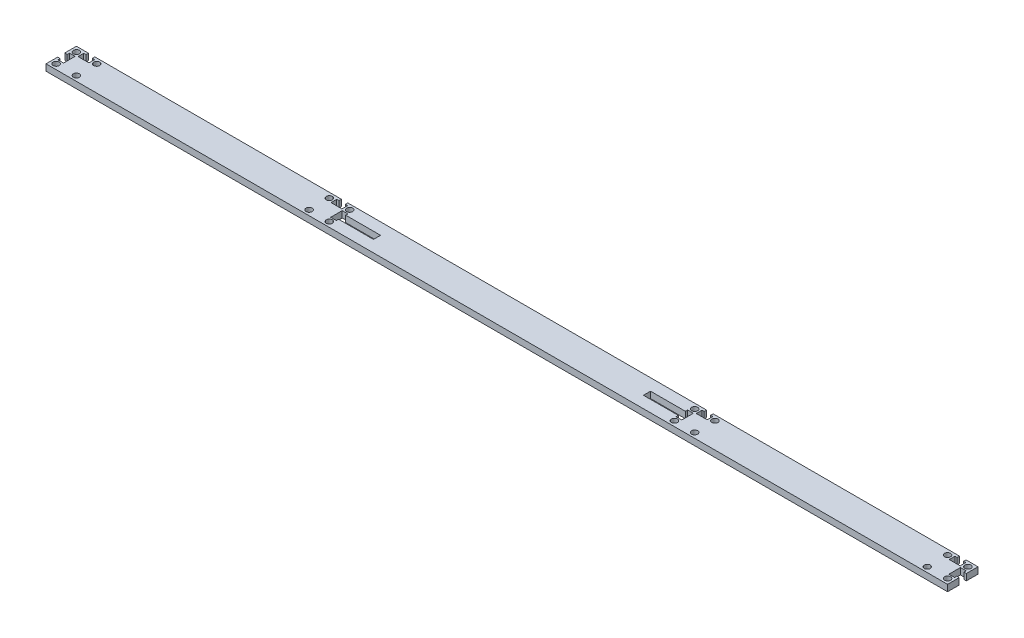
SolidWorks part; units mm, degrees
ref_plane "Front Plane" through (0, 0, 0) normal (0, 0, 1) x (1, 0, 0)
ref_plane "Top Plane" through (0, 0, 0) normal (0, 1, 0) x (1, 0, 0)
ref_plane "Right Plane" through (0, 0, 0) normal (1, 0, 0) x (0, 0, -1)
sketch "Sketch1" plane through (0, 0, 0) normal (0, 1, 0) x (1, 0, 0)
  line L0 (139.7, 7.5) -> (132.2, 7.5)
  line L1 (0, 0) -> (139.7, 0)
  line L2 (0, 0) -> (0, 15)
  line L3 (0, 15) -> (139.7, 15)
  line L4 (139.7, 0) -> (139.7, 15)
  line L5 (0, 7.5) -> (7.5, 7.5)
  line L6 (7.5, 7.5) -> (7.5, 12.5)
  line L7 (7.5, 12.5) -> (2.5, 12.5)
  line L8 (7.5, 12.5) -> (12.5, 12.5)
  line L9 (7.5, 7.5) -> (7.5, 2.5)
  line L10 (7.5, 2.5) -> (2.5, 2.5)
  line L11 (7.5, 2.5) -> (12.5, 2.5)
  line L12 (69.85, 0) -> (69.85, 15)
  line L13 (139.7, 0) -> (139.7, 15)
  line L14 (139.7, 0) -> (304.8, 0)
  line L15 (139.7, 15) -> (304.8, 15)
  line L16 (222.25, 0) -> (222.25, 15)
  line L17 (304.8, 0) -> (304.8, 15)
  line L18 (444.5, 15) -> (304.8, 15)
  line L19 (304.8, 0) -> (304.8, 15)
  line L20 (444.5, 0) -> (304.8, 0)
  line L21 (444.5, 0) -> (444.5, 15)
  circle A0 centre (2.5, 2.5) radius 1.5
  circle A1 centre (2.5, 12.5) radius 1.5
  circle A2 centre (12.5, 12.5) radius 1.5
  circle A3 centre (12.5, 2.5) radius 1.5
  circle A4 centre (137.2, 12.5) radius 1.5
  circle A5 centre (127.2, 12.5) radius 1.5
  circle A6 centre (137.2, 2.5) radius 1.5
  circle A7 centre (127.2, 2.5) radius 1.5
  circle A8 centre (432, 12.5) radius 1.5
  circle A9 centre (442, 12.5) radius 1.5
  circle A10 centre (442, 2.5) radius 1.5
  circle A11 centre (432, 2.5) radius 1.5
  circle A12 centre (307.3, 12.5) radius 1.5
  circle A13 centre (317.3, 12.5) radius 1.5
  circle A14 centre (317.3, 2.5) radius 1.5
  circle A15 centre (307.3, 2.5) radius 1.5
  dimension "D11" = 82.55
  dimension "D1" = 15
  dimension "D2" = 139.7
  dimension "D3" = 7.5
  dimension "D4" = 7.5
  dimension "D5" = 5
  dimension "D6" = 5
  dimension "D7" = 5
  dimension "D8" = 5
  dimension "D9" = 5
  dimension "D10" = 5
extrude "Boss-Extrude1" add sketch "Sketch1" along normal blind 3.175
sketch "Sketch23" plane through (0, 3.175, 0) normal (0, 1, 0) x (1, 0, 0)
  line L0 (0, 7.5) -> (0, 5.75)
  line L1 (0, 0) -> (0, 15) construction
  line L3 (0, 7.5) -> (0, 9.25)
  line L4 (0, 9.25) -> (0, 5.75)
  line L5 (0, 9.25) -> (1.2, 9.25)
  line L6 (0, 5.75) -> (1.2, 5.75)
  line L8 (1.2, 5.75) -> (1.2, 4.65)
  line L10 (1.2, 9.25) -> (1.2, 10.35)
  line L11 (1.2, 4.65) -> (4, 4.65)
  line L15 (1.2, 10.35) -> (4, 10.35)
  line L17 (4, 10.35) -> (4, 4.65)
  line L20 (127.2, 12.5) -> (12.5, 12.5)
  line L21 (69.85, 12.5) -> (69.85, 0)
  line L22 (0, 0) -> (444.5, 0) construction
  line L23 (7.5, 15) -> (9.0836, 15)
  line L24 (222.25, 15) -> (222.25, 0)
  line L25 (0, 15) -> (444.5, 15) construction
  line L26 (7.5, 15) -> (5.9043, 15)
  line L27 (5.9043, 15) -> (5.9043, 13.8)
  line L28 (5.9043, 13.8) -> (4.8043, 13.8)
  line L29 (4.8043, 13.8) -> (4.8043, 11)
  line L30 (4.8043, 11) -> (10.1836, 11)
  line L31 (10.1836, 11) -> (10.1836, 13.8)
  line L32 (10.1836, 13.8) -> (9.0836, 13.8)
  line L33 (9.0836, 13.8) -> (9.0836, 15)
  line L34 (132.2, 15) -> (133.7957, 15)
  line L35 (132.2, 15) -> (130.6164, 15)
  line L36 (130.6164, 13.8) -> (130.6164, 15)
  line L37 (129.5164, 13.8) -> (130.6164, 13.8)
  line L38 (129.5164, 11) -> (129.5164, 13.8)
  line L39 (134.8957, 11) -> (129.5164, 11)
  line L40 (134.8957, 13.8) -> (134.8957, 11)
  line L41 (133.7957, 13.8) -> (134.8957, 13.8)
  line L42 (133.7957, 15) -> (133.7957, 13.8)
  line L43 (138.5, 4.65) -> (135.7, 4.65)
  line L44 (138.5, 5.75) -> (138.5, 4.65)
  line L45 (139.7, 5.75) -> (138.5, 5.75)
  line L48 (139.7, 9.25) -> (138.5, 9.25)
  line L49 (138.5, 9.25) -> (138.5, 10.35)
  line L50 (138.5, 10.35) -> (135.7, 10.35)
  line L51 (135.7, 10.35) -> (135.7, 4.65)
  line L52 (444.5, 7.5) -> (444.5, 5.75)
  line L53 (444.5, 7.5) -> (444.5, 9.25)
  line L54 (440.5, 10.35) -> (440.5, 4.65)
  line L55 (306, 4.65) -> (308.8, 4.65)
  line L56 (306, 5.75) -> (306, 4.65)
  line L57 (304.8, 5.75) -> (306, 5.75)
  line L60 (304.8, 9.25) -> (306, 9.25)
  line L61 (306, 9.25) -> (306, 10.35)
  line L62 (306, 10.35) -> (308.8, 10.35)
  line L63 (308.8, 10.35) -> (308.8, 4.65)
  line L64 (309.6043, 13.8) -> (309.6043, 11)
  line L65 (310.7043, 13.8) -> (309.6043, 13.8)
  line L66 (310.7043, 15) -> (310.7043, 13.8)
  line L67 (312.3, 15) -> (310.7043, 15)
  line L68 (312.3, 15) -> (313.8836, 15)
  line L69 (313.8836, 13.8) -> (313.8836, 15)
  line L70 (314.9836, 13.8) -> (313.8836, 13.8)
  line L71 (314.9836, 11) -> (314.9836, 13.8)
  line L72 (309.6043, 11) -> (314.9836, 11)
  line L73 (443.3, 4.65) -> (440.5, 4.65)
  line L74 (443.3, 5.75) -> (443.3, 4.65)
  line L75 (444.5, 5.75) -> (443.3, 5.75)
  line L76 (444.5, 9.25) -> (443.3, 9.25)
  line L77 (443.3, 9.25) -> (443.3, 10.35)
  line L78 (443.3, 10.35) -> (440.5, 10.35)
  line L79 (439.6957, 11) -> (434.3164, 11)
  line L80 (434.3164, 11) -> (434.3164, 13.8)
  line L81 (434.3164, 13.8) -> (435.4164, 13.8)
  line L82 (435.4164, 13.8) -> (435.4164, 15)
  line L83 (437, 15) -> (435.4164, 15)
  line L84 (437, 15) -> (438.5957, 15)
  line L85 (438.5957, 15) -> (438.5957, 13.8)
  line L86 (438.5957, 13.8) -> (439.6957, 13.8)
  line L87 (439.6957, 13.8) -> (439.6957, 11)
  line L88 (304.8, 9.25) -> (288.8, 9.25)
  line L89 (288.8, 9.25) -> (288.8, 5.75)
  line L90 (288.8, 5.75) -> (304.8, 5.75)
  line L91 (139.7, 9.25) -> (155.7, 9.25)
  line L92 (155.7, 9.25) -> (155.7, 5.75)
  line L93 (155.7, 5.75) -> (139.7, 5.75)
  point P2 (5.1716, 7.5)
  dimension "D1" = 1.75
  dimension "D2" = 1.75
  dimension "D3" = 1.2
  dimension "D4" = 1.1
  dimension "D5" = 1.1
  dimension "D6" = 2.8
  dimension "D7" = 2.8
  dimension "D8" = 1.2
  dimension "D9" = 1.2
  dimension "D10" = 1.1
  dimension "D11" = 1.1
  dimension "D12" = 2.8
  dimension "D13" = 16
  dimension "D14" = 16
extrude "Cut-Extrude19" cut sketch "Sketch23" against normal through all
